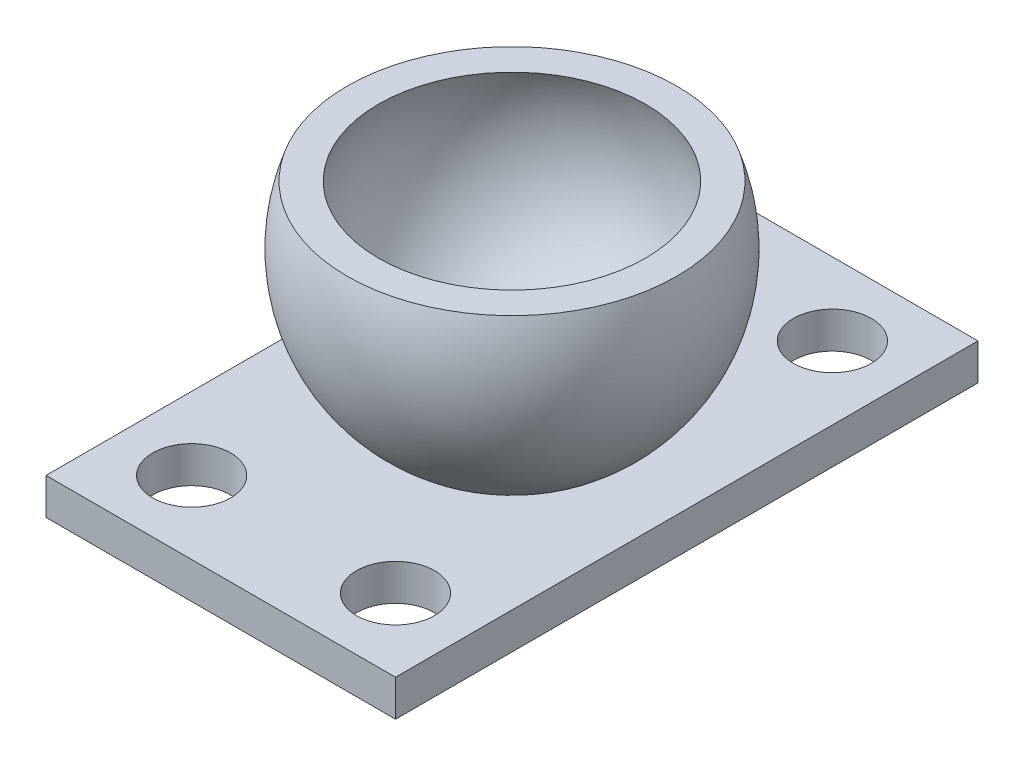
SolidWorks part; units mm, degrees
ref_plane "Front Plane" through (0, 0, 0) normal (0, 0, 1) x (1, 0, 0)
ref_plane "Top Plane" through (0, 0, 0) normal (0, 1, 0) x (1, 0, 0)
ref_plane "Right Plane" through (0, 0, 0) normal (1, 0, 0) x (0, 0, -1)
sketch "Sketch1" plane through (0, 0, 0) normal (0, 0, 1) x (1, 0, 0)
  line L0 (0, 7.62) -> (0, -7.62)
  arc A0 (0, -7.62) -> (0, 7.62) centre (0, 0) ccw
  dimension "D1" = 7.62
revolve "Revolve1" add sketch "Sketch1" angle 360 about L0
ref_plane "Plane1" through (0, 2.54, 0) normal (0, 1, 0) x (1, 0, 0)
sketch "Sketch2" plane through (0, 0, 0) normal (0, 0, 1) x (1, 0, 0)
  line L0 (8.382, 2.54) -> (-8.382, 2.54) construction
  line L2 (-8.89, 2.54) -> (8.89, 2.54)
  line L3 (-8.89, 2.54) -> (-8.89, 8.89)
  line L4 (-8.89, 8.89) -> (8.89, 8.89)
  line L5 (8.89, 2.54) -> (8.89, 8.89)
  point P6 (0, 2.54)
  dimension "D1" = 6.35
  dimension "D2" = 17.78
extrude "Cut-Extrude1" cut sketch "Sketch2" against normal mid plane 25.4
shell "Shell1" thickness 1.27
ref_plane "Plane2" through (0, -7.62, 0) normal (0, 1, 0) x (1, 0, 0)
sketch "Sketch3" plane through (0, -7.62, 0) normal (0, 1, 0) x (1, 0, 0)
  line L1 (-7.62, -12.7) -> (7.62, -12.7)
  line L2 (-7.62, -12.7) -> (-7.62, 12.7)
  line L3 (-7.62, 12.7) -> (7.62, 12.7)
  line L4 (7.62, -12.7) -> (7.62, 12.7)
  circle A0 centre (0, 0) radius 7.62 construction
  point P6 (7.62, 0)
  dimension "D1" = 25.4
extrude "Boss-Extrude1" add sketch "Sketch3" along normal blind 1.5875
sketch "Sketch4" plane through (0, -6.0325, 0) normal (0, 1, 0) x (1, 0, 0)
  line L0 (-7.62, 12.7) -> (-7.62, -12.7) construction
  line L1 (7.62, -12.7) -> (7.62, 12.7) construction
  line L2 (-7.62, -12.7) -> (7.62, -12.7) construction
  line L3 (7.62, 12.7) -> (-7.62, 12.7) construction
  point P0 (-4.445, 9.525)
  point P1 (4.445, 9.525)
  point P2 (4.445, -9.525)
  point P3 (-4.445, -9.525)
  point P12 (0, 0)
  point P13 (0, 0)
  point P14 (0, 0)
  point P15 (0, 0)
  point P16 (0, 0)
  point P17 (0, 0)
  dimension "D1" = 3.175
  dimension "D2" = 3.175
  dimension "D3" = 3.175
  dimension "D4" = 3.175
hole_wizard "M3 Clearance Hole1" positions "Sketch5" profile "Sketch6" hole size "M3" standard "ANSI Metric" end condition through all
sketch "Sketch5" plane through (0, -6.0325, 0) normal (0, 1, 0) x (1, 0, 0)
  point P0 (-4.445, -9.525)
  point P3 (-4.445, 9.525)
  point P6 (4.445, 9.525)
  point P9 (4.445, -9.525)
sketch "Sketch6" plane through (-4.445, -6.0325, 9.525) normal (1, 0, 0) x (0, 0, 1)
  line L0 (0, 0) -> (0, 1.5875)
  line L1 (0, 1.5875) -> (1.7, 1.5875)
  line L2 (1.7, 1.5875) -> (1.7, 0)
  line L5 (1.7, 0) -> (0, 0)
  line L11 (0, -6.35) -> (0, 107.95) construction
  dimension "Thru Hole Dia." = 3.4
  dimension "Thru Hole Depth" = 1.5875
